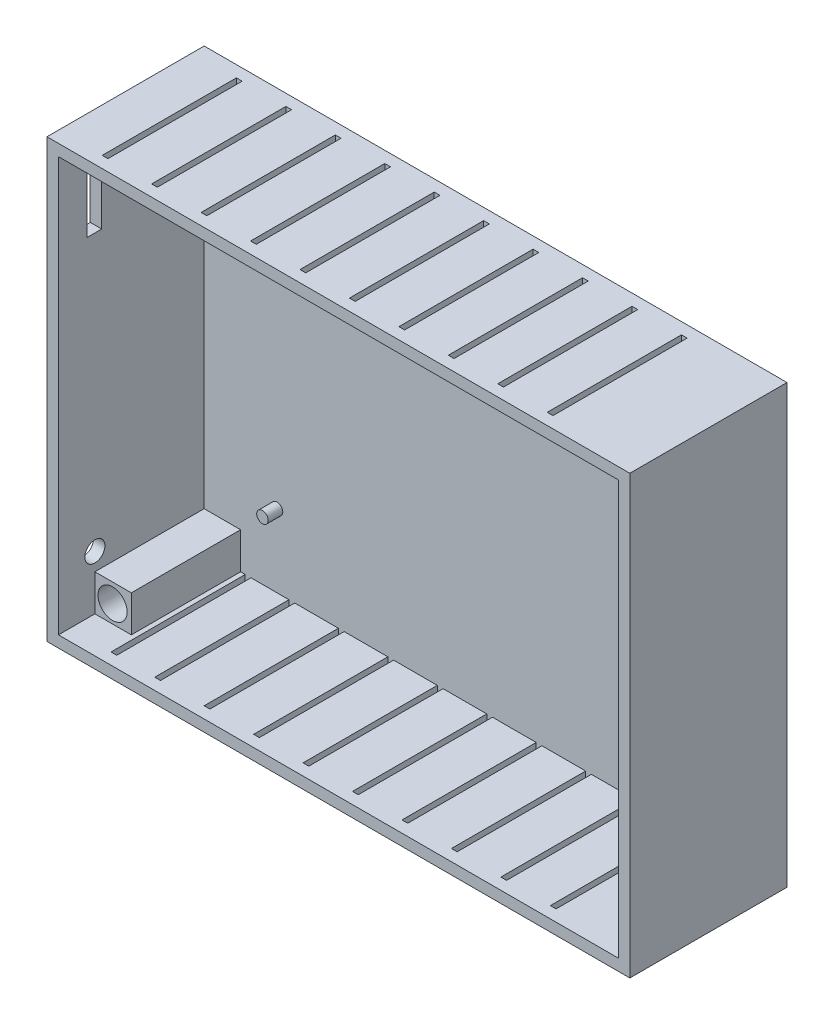
SolidWorks part; units mm, degrees
ref_plane "Front Plane" through (0, 0, 0) normal (0, 0, 1) x (1, 0, 0)
ref_plane "Top Plane" through (0, 0, 0) normal (0, 1, 0) x (1, 0, 0)
ref_plane "Right Plane" through (0, 0, 0) normal (1, 0, 0) x (0, 0, -1)
sketch "Sketch16" plane through (0, 0, 0) normal (0, 0, 1) x (1, 0, 0)
  line L1 (0, 0) -> (101.6, 0)
  line L2 (0, 0) -> (0, -76.2)
  line L3 (0, -76.2) -> (101.6, -76.2)
  line L4 (101.6, 0) -> (101.6, -76.2)
  dimension "D1" = 101.6
  dimension "D2" = 76.2
extrude "Boss-Extrude4" add sketch "Sketch16" along normal blind 2
sketch "Sketch17" plane through (0, 0, 2) normal (0, 0, 1) x (1, 0, 0)
  line L1 (0, 0) -> (101.6, 0)
  line L2 (0, 0) -> (0, -76.2)
  line L3 (0, -76.2) -> (101.6, -76.2)
  line L4 (101.6, 0) -> (101.6, -76.2)
  line L5 (2, -2) -> (99.6, -2)
  line L6 (2, -2) -> (2, -74.2)
  line L7 (2, -74.2) -> (99.6, -74.2)
  line L8 (99.6, -2) -> (99.6, -74.2)
  dimension "D1" = 2
  dimension "D2" = 2
  dimension "D3" = 2
  dimension "D4" = 2
extrude "Boss-Extrude5" add sketch "Sketch17" along normal blind 25.4
sketch "Sketch18" plane through (0, 0, 2) normal (0, 0, 1) x (1, 0, 0)
  line L0 (2, -74.2) -> (99.6, -74.2) construction
  line L1 (2, -2) -> (2, -74.2) construction
  line L2 (99.6, -2) -> (2, -2) construction
  line L3 (99.6, -74.2) -> (99.6, -2) construction
  line L4 (99.6, -74.2) -> (99.6, -2) construction
  line L5 (2, -74.2) -> (99.6, -74.2) construction
  circle A0 centre (14.7, -14.7) radius 1
  circle A1 centre (86.9, -14.7) radius 1
  circle A2 centre (86.9, -61.5) radius 1
  circle A3 centre (14.7, -61.5) radius 1
  dimension "D1" = 2
  dimension "D2" = 2
  dimension "D3" = 2
  dimension "D4" = 2
  dimension "D5" = 12.7
  dimension "D10" = 12.7
  dimension "D6" = 12.7
  dimension "D7" = 12.7
  dimension "D8" = 12.7
  dimension "D9" = 12.7
  dimension "D11" = 12.7
  dimension "D12" = 12.7
extrude "Boss-Extrude6" add sketch "Sketch18" along normal blind 2.54
sketch "Sketch19" plane through (0, -76.2, 0) normal (0, -1, 0) x (1, 0, 0)
  line L0 (0, 27.4) -> (101.6, 27.4) construction
  line L1 (10.16, 25.4) -> (9.16, 25.4)
  line L2 (10.16, 25.4) -> (10.16, 2)
  line L3 (10.16, 2) -> (9.16, 2)
  line L4 (9.16, 25.4) -> (9.16, 2)
  line L5 (17.78, 25.4) -> (16.78, 25.4)
  line L6 (17.78, 25.4) -> (17.78, 2)
  line L7 (17.78, 2) -> (16.78, 2)
  line L8 (16.78, 25.4) -> (16.78, 2)
  line L9 (25.4, 25.4) -> (26.4, 25.4)
  line L10 (25.4, 25.4) -> (25.4, 2)
  line L11 (25.4, 2) -> (26.4, 2)
  line L12 (26.4, 25.4) -> (26.4, 2)
  line L13 (34.02, 25.4) -> (35.02, 25.4)
  line L14 (34.02, 25.4) -> (34.02, 2)
  line L15 (34.02, 2) -> (35.02, 2)
  line L16 (35.02, 25.4) -> (35.02, 2)
  line L17 (42.64, 25.4) -> (43.64, 25.4)
  line L18 (42.64, 25.4) -> (42.64, 2)
  line L19 (42.64, 2) -> (43.64, 2)
  line L20 (43.64, 25.4) -> (43.64, 2)
  line L21 (51.26, 25.4) -> (52.26, 25.4)
  line L22 (51.26, 25.4) -> (51.26, 2)
  line L23 (51.26, 2) -> (52.26, 2)
  line L24 (52.26, 25.4) -> (52.26, 2)
  line L25 (59.88, 25.4) -> (60.88, 25.4)
  line L26 (59.88, 25.4) -> (59.88, 2)
  line L27 (59.88, 2) -> (60.88, 2)
  line L28 (60.88, 25.4) -> (60.88, 2)
  line L29 (68.5, 25.4) -> (69.5, 25.4)
  line L30 (68.5, 25.4) -> (68.5, 2)
  line L31 (68.5, 2) -> (69.5, 2)
  line L32 (69.5, 25.4) -> (69.5, 2)
  line L33 (77.12, 25.4) -> (78.12, 25.4)
  line L34 (77.12, 25.4) -> (77.12, 2)
  line L35 (77.12, 2) -> (78.12, 2)
  line L36 (78.12, 25.4) -> (78.12, 2)
  line L37 (85.74, 25.4) -> (86.74, 25.4)
  line L38 (85.74, 25.4) -> (85.74, 2)
  line L39 (85.74, 2) -> (86.74, 2)
  line L40 (86.74, 25.4) -> (86.74, 2)
  line L41 (0, 0) -> (101.6, 0) construction
  line L44 (0, 27.4) -> (0, 0) construction
  dimension "D2" = 7.62
  dimension "D3" = 7.62
  dimension "D4" = 7.62
  dimension "D5" = 7.62
  dimension "D6" = 7.62
  dimension "D7" = 7.62
  dimension "D8" = 7.62
  dimension "D9" = 7.62
  dimension "D10" = 10.16
  dimension "D11" = 2
  dimension "D12" = 7.62
  dimension "D13" = 1
  dimension "D14" = 2
  dimension "D15" = 2
  dimension "D16" = 2
  dimension "D17" = 2
  dimension "D18" = 2
  dimension "D19" = 2
  dimension "D20" = 2
  dimension "D21" = 2
  dimension "D22" = 2
  dimension "D23" = 2
extrude "Cut-Extrude6" cut sketch "Sketch19" against normal blind 2
sketch "Sketch20" plane through (0, 0, 0) normal (0, 1, 0) x (1, 0, 0)
  line L1 (7.62, -2) -> (8.62, -2)
  line L2 (7.62, -2) -> (7.62, -25.4)
  line L3 (7.62, -25.4) -> (8.62, -25.4)
  line L4 (8.62, -2) -> (8.62, -25.4)
  line L5 (16.24, -2) -> (17.24, -2)
  line L6 (16.24, -2) -> (16.24, -25.4)
  line L7 (16.24, -25.4) -> (17.24, -25.4)
  line L8 (17.24, -2) -> (17.24, -25.4)
  line L9 (24.86, -2) -> (25.86, -2)
  line L10 (24.86, -2) -> (24.86, -25.4)
  line L11 (24.86, -25.4) -> (25.86, -25.4)
  line L12 (25.86, -2) -> (25.86, -25.4)
  line L13 (33.48, -2) -> (34.48, -2)
  line L14 (33.48, -2) -> (33.48, -25.4)
  line L15 (33.48, -25.4) -> (34.48, -25.4)
  line L16 (34.48, -2) -> (34.48, -25.4)
  line L17 (42.1, -2) -> (43.1, -2)
  line L18 (42.1, -2) -> (42.1, -25.4)
  line L19 (42.1, -25.4) -> (43.1, -25.4)
  line L20 (43.1, -2) -> (43.1, -25.4)
  line L21 (50.72, -2) -> (51.72, -2)
  line L22 (50.72, -2) -> (50.72, -25.4)
  line L23 (50.72, -25.4) -> (51.72, -25.4)
  line L24 (51.72, -2) -> (51.72, -25.4)
  line L25 (59.34, -2) -> (60.34, -2)
  line L26 (59.34, -2) -> (59.34, -25.4)
  line L27 (59.34, -25.4) -> (60.34, -25.4)
  line L28 (60.34, -2) -> (60.34, -25.4)
  line L29 (67.96, -2) -> (68.96, -2)
  line L30 (67.96, -2) -> (67.96, -25.4)
  line L31 (67.96, -25.4) -> (68.96, -25.4)
  line L32 (68.96, -2) -> (68.96, -25.4)
  line L33 (85.2, -2) -> (86.2, -2)
  line L34 (85.2, -2) -> (85.2, -25.4)
  line L35 (85.2, -25.4) -> (86.2, -25.4)
  line L36 (86.2, -2) -> (86.2, -25.4)
  line L37 (77.58, -2) -> (76.58, -2)
  line L38 (77.58, -2) -> (77.58, -25.4)
  line L39 (77.58, -25.4) -> (76.58, -25.4)
  line L40 (76.58, -2) -> (76.58, -25.4)
  line L41 (0, -27.4) -> (0, 0) construction
  line L42 (101.6, -27.4) -> (0, -27.4) construction
  line L43 (101.6, 0) -> (0, 0) construction
  dimension "D1" = 7.62
  dimension "D2" = 7.62
  dimension "D3" = 7.62
  dimension "D4" = 1
  dimension "D5" = 7.62
  dimension "D6" = 7.62
  dimension "D7" = 7.62
  dimension "D8" = 7.62
  dimension "D9" = 7.62
  dimension "D10" = 7.62
  dimension "D11" = 7.62
  dimension "D12" = 2
  dimension "D13" = 2
  dimension "D14" = 2
  dimension "D15" = 2
  dimension "D16" = 2
  dimension "D17" = 2
  dimension "D18" = 2
  dimension "D19" = 2
  dimension "D20" = 2
  dimension "D21" = 2
  dimension "D22" = 2
  dimension "D23" = 2
  dimension "D24" = 2
  dimension "D25" = 2
  dimension "D26" = 2
  dimension "D27" = 2
  dimension "D28" = 2
  dimension "D29" = 2
  dimension "D30" = 2
  dimension "D31" = 2
extrude "Cut-Extrude7" cut sketch "Sketch20" against normal blind 2
sketch "Sketch21" plane through (0, 0, 0) normal (-1, 0, 0) x (0, 0, 1)
  line L0 (27.4, 0) -> (27.4, -76.2) construction
  line L1 (19.86, -4) -> (22.4, -4)
  line L2 (19.86, -4) -> (19.86, -16.7)
  line L3 (19.86, -16.7) -> (22.4, -16.7)
  line L4 (22.4, -4) -> (22.4, -16.7)
  line L5 (27.4, 0) -> (0, 0) construction
  line L6 (27.4, -76.2) -> (0, -76.2) construction
  circle A0 centre (21.05, -64.77) radius 1.75
  dimension "D5" = 3.5
  dimension "D1" = 12.7
  dimension "D2" = 5
  dimension "D3" = 4
  dimension "D4" = 2.54
  dimension "D6" = 6.35
  dimension "D7" = 11.43
extrude "Cut-Extrude8" cut sketch "Sketch21" against normal blind 2
sketch "Sketch22" plane through (0, -76.2, 0) normal (0, -1, 0) x (1, 0, 0)
  line L0 (101.6, 27.4) -> (101.6, 0) construction
  line L1 (101.6, 25.65) -> (1, 25.65)
  line L2 (101.6, 25.65) -> (101.6, 26.65)
  line L3 (101.6, 26.65) -> (1, 26.65)
  line L4 (1, 25.65) -> (1, 26.65)
  line L5 (0, 27.4) -> (101.6, 27.4) construction
  line L6 (0, 27.4) -> (0, 0) construction
  dimension "D1" = 1
  dimension "D2" = 0.75
  dimension "D3" = 1
sketch "Sketch23" plane through (0, 0, 0) normal (0, 1, 0) x (1, 0, 0)
  line L0 (0, -27.4) -> (0, 0) construction
  line L1 (101.6, -27.4) -> (1, -27.4)
  line L2 (101.6, -27.4) -> (101.6, -26.65)
  line L3 (101.6, -26.65) -> (1, -26.65)
  line L4 (1, -27.4) -> (1, -26.65)
  dimension "D1" = 0.75
  dimension "D2" = 1
sketch "Sketch33" plane through (0, 0, 2) normal (0, 0, 1) x (1, 0, 0)
  line L0 (101.6, -76.2) -> (101.6, 0) construction
  line L1 (2, -2) -> (8.35, -2)
  line L2 (2, -2) -> (2, -8.35)
  line L3 (2, -8.35) -> (8.35, -8.35)
  line L4 (8.35, -2) -> (8.35, -8.35)
  line L5 (99.6, -2) -> (93.25, -2)
  line L6 (99.6, -2) -> (99.6, -8.35)
  line L7 (99.6, -8.35) -> (93.25, -8.35)
  line L8 (93.25, -2) -> (93.25, -8.35)
  line L9 (2, -74.2) -> (8.35, -74.2)
  line L10 (2, -74.2) -> (2, -67.85)
  line L11 (2, -67.85) -> (8.35, -67.85)
  line L12 (8.35, -74.2) -> (8.35, -67.85)
  line L13 (99.6, -74.2) -> (93.25, -74.2)
  line L14 (99.6, -74.2) -> (99.6, -67.85)
  line L15 (99.6, -67.85) -> (93.25, -67.85)
  line L16 (93.25, -74.2) -> (93.25, -67.85)
  line L18 (101.6, -76.2) -> (1, -76.2) construction
  line L19 (0, 0) -> (0, -76.2) construction
  line L20 (101.6, 0) -> (0, 0) construction
  line L21 (0, 0) -> (0, -76.2) construction
  circle A0 centre (5.08, -5.08) radius 2.54
  circle A1 centre (5.08, -71.12) radius 2.54
  circle A2 centre (96.52, -71.12) radius 2.54
  circle A3 centre (96.52, -5.08) radius 2.54
  point P38 (-0.1217, -5.658)
  dimension "D9" = 5.08
  dimension "D10" = 5.08
  dimension "D11" = 5.08
  dimension "D12" = 5.08
  dimension "D1" = 6.35
  dimension "D2" = 6.35
  dimension "D3" = 6.35
  dimension "D4" = 6.35
  dimension "D5" = 6.35
  dimension "D6" = 6.35
  dimension "D7" = 6.35
  dimension "D8" = 6.35
  dimension "D13" = 5.08
  dimension "D14" = 5.08
  dimension "D15" = 5.08
  dimension "D16" = 5.08
  dimension "D17" = 5.08
  dimension "D18" = 5.08
  dimension "D19" = 5.08
  dimension "D20" = 5.08
extrude "Boss-Extrude7" add sketch "Sketch33" along normal blind 19.05
